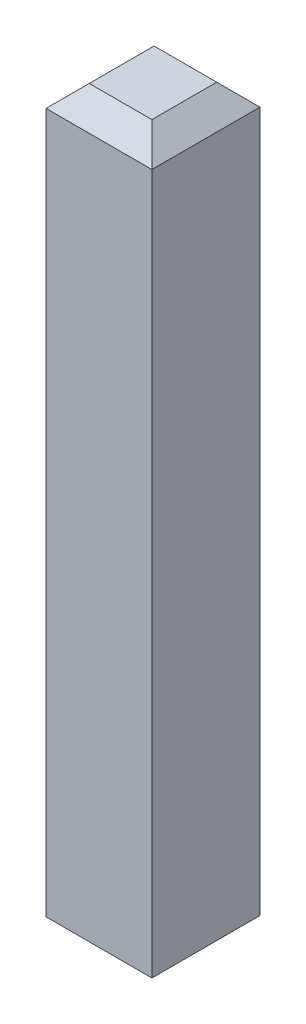
SolidWorks part; units mm, degrees
ref_plane "Front Plane" through (0, 0, 0) normal (0, 0, 1) x (1, 0, 0)
ref_plane "Top Plane" through (0, 0, 0) normal (0, 1, 0) x (1, 0, 0)
ref_plane "Right Plane" through (0, 0, 0) normal (1, 0, 0) x (0, 0, -1)
sketch "Sketch1" plane through (0, 0, 0) normal (0, 1, 0) x (1, 0, 0)
  line L1 (0, 0) -> (4.9, 0)
  line L2 (0, 0) -> (0, 5)
  line L3 (0, 5) -> (4.9, 5)
  line L4 (4.9, 0) -> (4.9, 5)
  dimension "D1" = 4.9
  dimension "D2" = 5
extrude "Boss-Extrude1" add sketch "Sketch1" along normal mid plane 33.4
chamfer "Chamfer1" distance 1 angle 45 4 edges at (2.45, 16.7, -5) (4.9, 16.7, -2.5) (2.45, 16.7, 0) (0, 16.7, -2.5)
